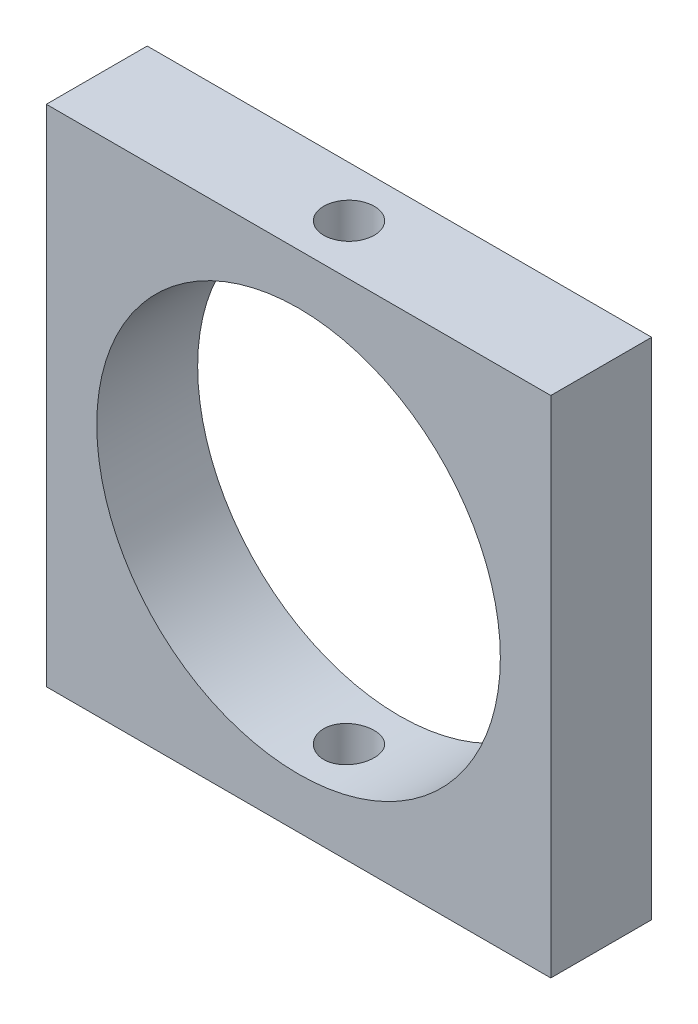
SolidWorks part; units mm, degrees
material "1060 Alloy"
ref_plane "Front Plane" through (0, 0, 0) normal (0, 0, 1) x (1, 0, 0)
ref_plane "Top Plane" through (0, 0, 0) normal (0, 1, 0) x (1, 0, 0)
ref_plane "Right Plane" through (0, 0, 0) normal (1, 0, 0) x (0, 0, -1)
sketch "Sketch1" plane through (0, 0, 0) normal (0, 0, 1) x (1, 0, 0)
  line L1 (-10, -10) -> (10, -10)
  line L2 (-10, -10) -> (-10, 10)
  line L3 (-10, 10) -> (10, 10)
  line L4 (10, -10) -> (10, 10)
  line L5 (-10, -10) -> (10, 10) construction
  line L6 (-10, 10) -> (10, -10) construction
  circle A0 centre (0, 0) radius 8
  point P0 (0, 0)
extrude "Boss-Extrude1" add sketch "Sketch1" along normal blind 4
sketch "Sketch3" plane through (0, 10, 0) normal (0, 1, 0) x (1, 0, 0)
  circle A0 centre (0, -2) radius 1
extrude "Cut-Extrude1" cut sketch "Sketch3" against normal blind 20
